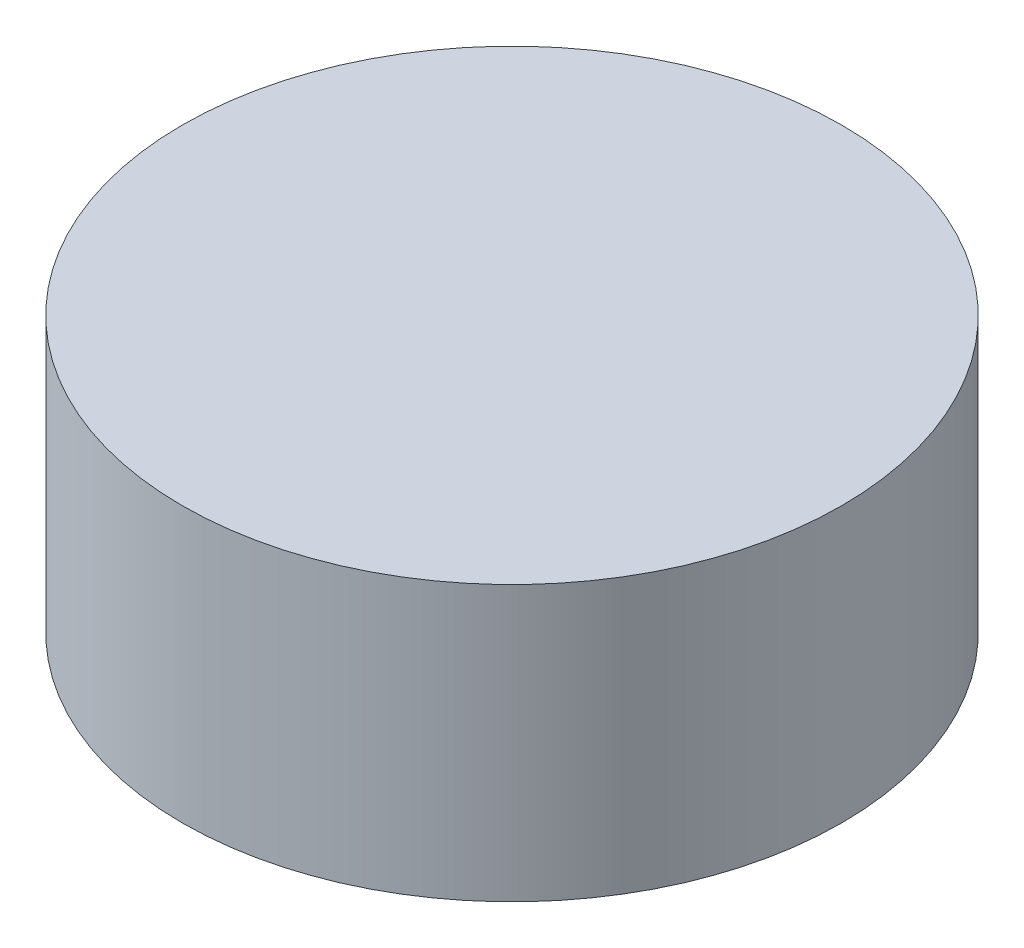
SolidWorks part; units mm, degrees
ref_plane "前视基准面" through (0, 0, 0) normal (0, 0, 1) x (1, 0, 0)
ref_plane "上视基准面" through (0, 0, 0) normal (0, 1, 0) x (1, 0, 0)
ref_plane "右视基准面" through (0, 0, 0) normal (1, 0, 0) x (0, 0, -1)
sketch "Sketch1" plane through (0, 0, 0) normal (0, 1, 0) x (1, 0, 0)
  circle A0 centre (0, 0) radius 3
extrude "Boss-Extrude1" add sketch "Sketch1" along normal blind 2.5
